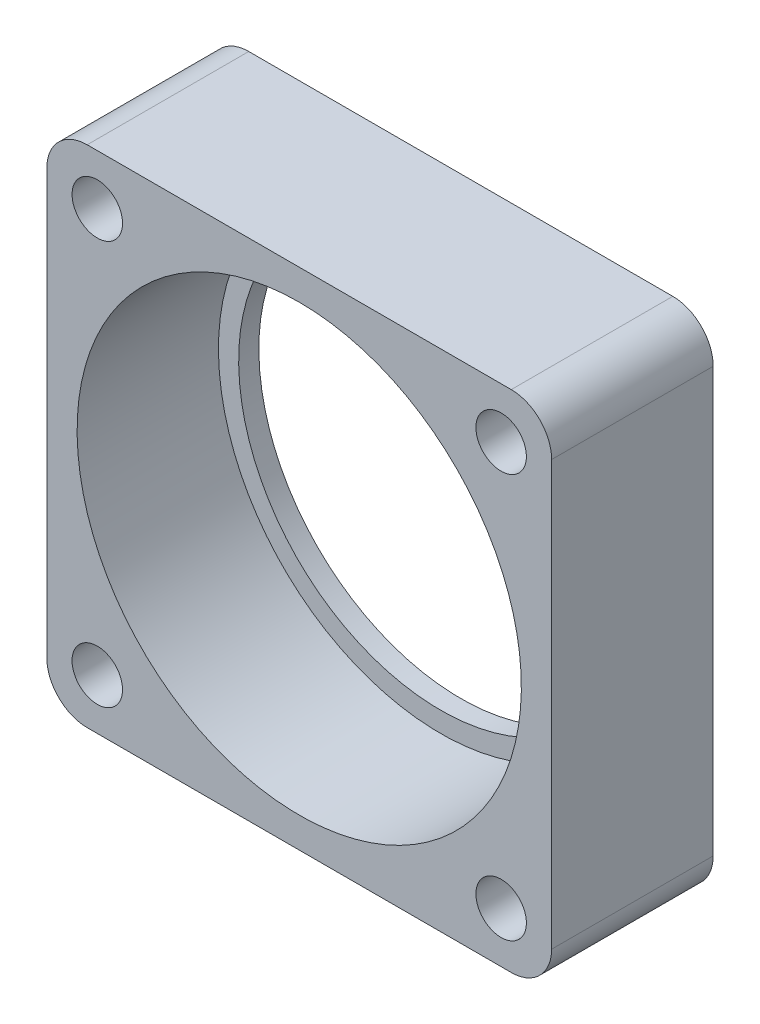
SolidWorks part; units mm, degrees
material "ABS"
ref_plane "Plan de face" through (0, 0, 0) normal (0, 0, 1) x (1, 0, 0)
ref_plane "Plan de dessus" through (0, 0, 0) normal (0, 1, 0) x (1, 0, 0)
ref_plane "Plan de droite" through (0, 0, 0) normal (1, 0, 0) x (0, 0, -1)
sketch "Esquisse1" plane through (0, 0, 0) normal (0, 0, 1) x (1, 0, 0)
  line L0 (0, 12.5) -> (0, 0) construction
  line L1 (-12.5, 12.5) -> (12.5, 12.5)
  line L2 (-12.5, 12.5) -> (-12.5, -12.5)
  line L3 (-12.5, -12.5) -> (12.5, -12.5)
  line L4 (12.5, 12.5) -> (12.5, -12.5)
  line L5 (0, 0) -> (-12.5, 0) construction
  circle A0 centre (-10, 10) radius 1.25
  circle A1 centre (10, 10) radius 1.25
  circle A2 centre (10, -10) radius 1.25
  circle A3 centre (-10, -10) radius 1.25
  circle A4 centre (-10, 10) radius 2.5 construction
  dimension "D1" = 2.5
  dimension "D2" = 20
  dimension "D3" = 25
extrude "Boss.-Extru.1" add sketch "Esquisse1" along normal blind 8
sketch "Esquisse2" plane through (0, 0, 0) normal (1, 0, 0) x (0, 0, -1)
  line L0 (-8, 0) -> (0, 0)
  line L1 (-8, -12.5) -> (-8, 12.5) construction
  line L2 (0, 0) -> (0, 10)
  line L3 (0, -12.5) -> (0, 12.5) construction
  line L4 (0, 10) -> (-1, 10)
  line L5 (-1, 10) -> (-1, 11)
  line L6 (-1, 11) -> (-8, 11)
  line L7 (-8, 11) -> (-8, 0)
  line L8 (-8, 0) -> (-16, 0) construction
  dimension "D1" = 1
  dimension "D2" = 7
  dimension "D3" = 22
revolve "Enlèvement de matière-Révolution1" cut sketch "Esquisse2" angle 360 about L8
fillet "Congé1" radius 2 4 edges at (-12.5, 12.5, 4) (12.5, -12.5, 4) (-12.5, -12.5, 4) (12.5, 12.5, 4)
